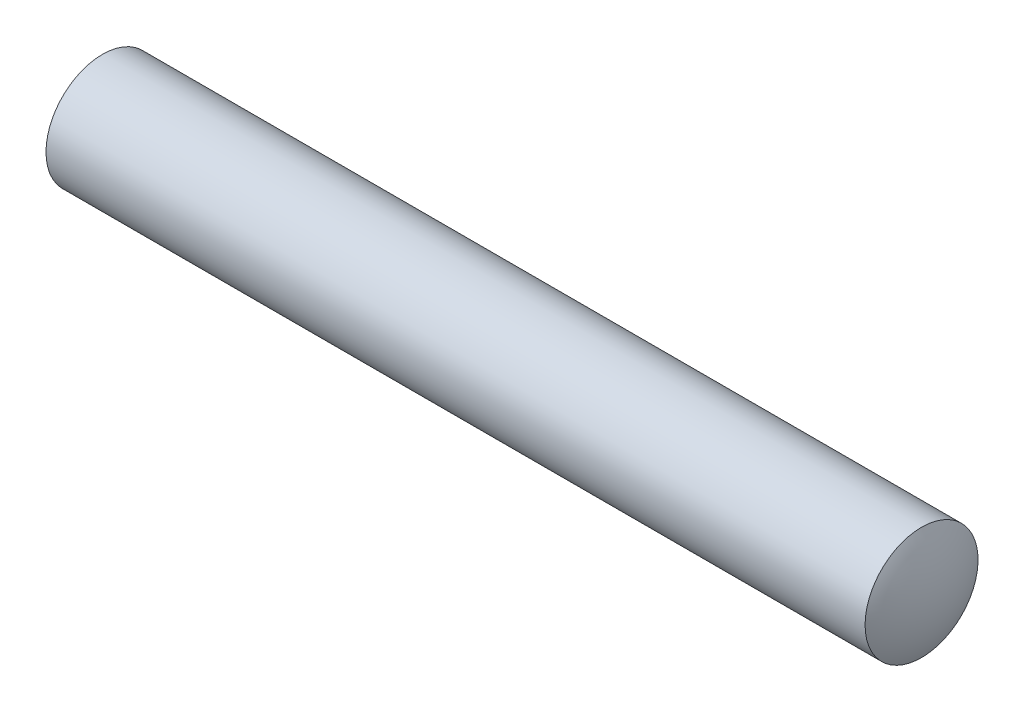
SolidWorks part; units mm, degrees
material "Простая углеродистая сталь"
ref_plane "Спереди" through (0, 0, 0) normal (0, 0, 1) x (1, 0, 0)
ref_plane "Сверху" through (0, 0, 0) normal (0, 1, 0) x (1, 0, 0)
ref_plane "Справа" through (0, 0, 0) normal (1, 0, 0) x (0, 0, -1)
sketch "Эскиз1" plane through (0, 0, 0) normal (0, 0, 1) x (1, 0, 0)
  line L0 (-31.9881, 0) -> (2.172, 0) construction
  line L1 (-0.5, 2) -> (-29.5, 2)
  line L3 (-30, 0) -> (0, 0)
  arc A0 (0, 0) -> (-0.5, 2) centre (-4.25, 0) ccw
  arc A1 (-29.5, 2) -> (-30, 0) centre (-25.75, 0) ccw
  dimension "D1" = 4
  dimension "D2" = 30
  dimension "D3" = 0.5
revolve "Повернуть1" add sketch "Эскиз1" angle 360 about L0
